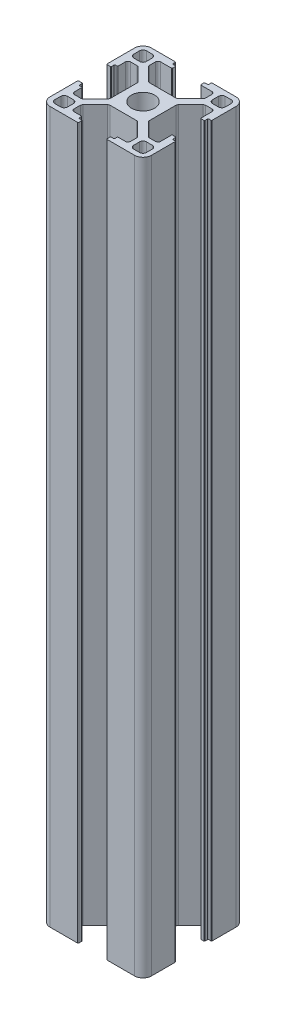
SolidWorks part; units mm, degrees
ref_plane "Front Plane" through (0, 0, 0) normal (0, 0, 1) x (1, 0, 0)
ref_plane "Top Plane" through (0, 0, 0) normal (0, 1, 0) x (1, 0, 0)
ref_plane "Right Plane" through (0, 0, 0) normal (1, 0, 0) x (0, 0, -1)
sketch "Sketch2" plane through (0, -1630.4411, 0) normal (0, 1, 0) x (1, 0, 0)
  line L4 (-1206.0668, -28.55) -> (-1204.3168, -28.55)
  line L5 (-1203.3168, -27.55) -> (-1203.3168, -25.8)
  line L6 (-1204.3168, -24.8) -> (-1206.0668, -24.8)
  line L7 (-1207.0668, -25.8) -> (-1207.0668, -27.55)
  line L8 (-1206.0668, -28.55) -> (-1204.3168, -28.55)
  line L9 (-1203.3168, -27.55) -> (-1203.3168, -25.8)
  line L10 (-1204.3168, -24.8) -> (-1206.0668, -24.8)
  line L11 (-1207.0668, -25.8) -> (-1207.0668, -27.55)
  line L12 (-1206.0668, -5.2) -> (-1204.3168, -5.2)
  line L13 (-1203.3168, -4.2) -> (-1203.3168, -2.45)
  line L14 (-1204.3168, -1.45) -> (-1206.0668, -1.45)
  line L15 (-1207.0668, -2.45) -> (-1207.0668, -4.2)
  line L16 (-1206.0668, -5.2) -> (-1204.3168, -5.2)
  line L17 (-1203.3168, -4.2) -> (-1203.3168, -2.45)
  line L18 (-1204.3168, -1.45) -> (-1206.0668, -1.45)
  line L19 (-1207.0668, -2.45) -> (-1207.0668, -4.2)
  line L20 (-1180.9668, -24.8) -> (-1182.7168, -24.8)
  line L21 (-1183.7168, -25.8) -> (-1183.7168, -27.55)
  line L22 (-1182.7168, -28.55) -> (-1180.9668, -28.55)
  line L23 (-1179.9668, -27.55) -> (-1179.9668, -25.8)
  line L24 (-1180.9668, -24.8) -> (-1182.7168, -24.8)
  line L25 (-1183.7168, -25.8) -> (-1183.7168, -27.55)
  line L26 (-1182.7168, -28.55) -> (-1180.9668, -28.55)
  line L27 (-1179.9668, -27.55) -> (-1179.9668, -25.8)
  line L28 (-1182.7168, -5.2) -> (-1180.9668, -5.2)
  line L29 (-1179.9668, -4.2) -> (-1179.9668, -2.45)
  line L30 (-1180.9668, -1.45) -> (-1182.7168, -1.45)
  line L31 (-1183.7168, -2.45) -> (-1183.7168, -4.2)
  line L32 (-1182.7168, -5.2) -> (-1180.9668, -5.2)
  line L33 (-1179.9668, -4.2) -> (-1179.9668, -2.45)
  line L34 (-1180.9668, -1.45) -> (-1182.7168, -1.45)
  line L35 (-1183.7168, -2.45) -> (-1183.7168, -4.2)
  line L60 (-1199.0168, 0) -> (-1206.0168, 0)
  line L61 (-1198.8168, -0.8) -> (-1198.8168, -0.2)
  line L62 (-1197.9168, -1) -> (-1198.6168, -1)
  line L63 (-1197.7168, -2) -> (-1197.7168, -1.2)
  line L64 (-1201.1168, -2.2) -> (-1197.9168, -2.2)
  line L65 (-1201.8668, -4.7837) -> (-1201.8668, -2.95)
  line L66 (-1197.9808, -8.9803) -> (-1201.6471, -5.314)
  line L67 (-1189.5831, -9.2) -> (-1197.4505, -9.2)
  line L68 (-1185.3865, -5.314) -> (-1189.0528, -8.9803)
  line L69 (-1185.1668, -2.95) -> (-1185.1668, -4.7837)
  line L70 (-1189.1168, -2.2) -> (-1185.9168, -2.2)
  line L71 (-1189.3168, -1.2) -> (-1189.3168, -2)
  line L72 (-1188.4168, -1) -> (-1189.1168, -1)
  line L73 (-1188.2168, -0.2) -> (-1188.2168, -0.8)
  line L74 (-1181.0168, 0) -> (-1188.0168, 0)
  line L75 (-1178.5168, -9.5) -> (-1178.5168, -2.5)
  line L76 (-1179.3168, -9.7) -> (-1178.7168, -9.7)
  line L77 (-1179.5168, -10.6) -> (-1179.5168, -9.9)
  line L78 (-1180.5168, -10.8) -> (-1179.7168, -10.8)
  line L79 (-1180.7168, -7.4) -> (-1180.7168, -10.6)
  line L80 (-1183.3005, -6.65) -> (-1181.4668, -6.65)
  line L81 (-1187.4971, -10.536) -> (-1183.8308, -6.8697)
  line L82 (-1187.7168, -18.9337) -> (-1187.7168, -11.0663)
  line L83 (-1183.8308, -23.1303) -> (-1187.4971, -19.464)
  line L84 (-1181.4668, -23.35) -> (-1183.3005, -23.35)
  line L85 (-1180.7168, -19.4) -> (-1180.7168, -22.6)
  line L86 (-1179.7168, -19.2) -> (-1180.5168, -19.2)
  line L87 (-1179.5168, -20.1) -> (-1179.5168, -19.4)
  line L88 (-1178.7168, -20.3) -> (-1179.3168, -20.3)
  line L89 (-1178.5168, -27.5) -> (-1178.5168, -20.5)
  line L90 (-1189.1168, -30) -> (-1181.0168, -30)
  line L91 (-1189.3168, -29) -> (-1189.3168, -29.8)
  line L92 (-1188.4168, -28.8) -> (-1189.1168, -28.8)
  line L93 (-1188.2168, -28) -> (-1188.2168, -28.6)
  line L94 (-1185.9168, -27.8) -> (-1188.0168, -27.8)
  line L95 (-1185.1668, -25.2163) -> (-1185.1668, -27.05)
  line L96 (-1189.0528, -21.0197) -> (-1185.3865, -24.686)
  line L97 (-1197.4505, -20.8) -> (-1189.5831, -20.8)
  line L98 (-1201.6471, -24.686) -> (-1197.9808, -21.0197)
  line L99 (-1201.8668, -27.05) -> (-1201.8668, -25.2163)
  line L100 (-1199.0168, -27.8) -> (-1201.1168, -27.8)
  line L101 (-1198.8168, -28.6) -> (-1198.8168, -28)
  line L102 (-1197.9168, -28.8) -> (-1198.6168, -28.8)
  line L103 (-1197.7168, -29.8) -> (-1197.7168, -29)
  line L104 (-1206.0168, -30) -> (-1197.9168, -30)
  line L105 (-1208.5168, -19.4) -> (-1208.5168, -27.5)
  line L106 (-1207.3844, -19.2) -> (-1208.3168, -19.2)
  line L107 (-1207.1844, -20.1) -> (-1207.1844, -19.4)
  line L108 (-1206.3844, -20.3) -> (-1206.9844, -20.3)
  line L109 (-1206.1844, -22.6) -> (-1206.1844, -20.5)
  line L110 (-1203.6007, -23.35) -> (-1205.4344, -23.35)
  line L111 (-1199.404, -19.464) -> (-1203.0703, -23.1303)
  line L112 (-1199.1844, -11.0663) -> (-1199.1844, -18.9337)
  line L113 (-1203.0703, -6.8697) -> (-1199.404, -10.536)
  line L114 (-1205.5668, -6.65) -> (-1203.6007, -6.65)
  line L115 (-1206.3168, -9.5) -> (-1206.3168, -7.4)
  line L116 (-1206.9844, -9.7) -> (-1206.5168, -9.7)
  line L117 (-1207.1844, -10.6) -> (-1207.1844, -9.9)
  line L118 (-1208.3168, -10.8) -> (-1207.3844, -10.8)
  line L119 (-1208.5168, -2.5) -> (-1208.5168, -10.6)
  line L120 (-1199.0168, 0) -> (-1206.0168, 0)
  line L121 (-1198.8168, -0.8) -> (-1198.8168, -0.2)
  line L122 (-1197.9168, -1) -> (-1198.6168, -1)
  line L123 (-1197.7168, -2) -> (-1197.7168, -1.2)
  line L124 (-1201.1168, -2.2) -> (-1197.9168, -2.2)
  line L125 (-1201.8668, -4.7837) -> (-1201.8668, -2.95)
  line L126 (-1197.9808, -8.9803) -> (-1201.6471, -5.314)
  line L127 (-1189.5831, -9.2) -> (-1197.4505, -9.2)
  line L128 (-1185.3865, -5.314) -> (-1189.0528, -8.9803)
  line L129 (-1185.1668, -2.95) -> (-1185.1668, -4.7837)
  line L130 (-1189.1168, -2.2) -> (-1185.9168, -2.2)
  line L131 (-1189.3168, -1.2) -> (-1189.3168, -2)
  line L132 (-1188.4168, -1) -> (-1189.1168, -1)
  line L133 (-1188.2168, -0.2) -> (-1188.2168, -0.8)
  line L134 (-1181.0168, 0) -> (-1188.0168, 0)
  line L135 (-1178.5168, -9.5) -> (-1178.5168, -2.5)
  line L136 (-1179.3168, -9.7) -> (-1178.7168, -9.7)
  line L137 (-1179.5168, -10.6) -> (-1179.5168, -9.9)
  line L138 (-1180.5168, -10.8) -> (-1179.7168, -10.8)
  line L139 (-1180.7168, -7.4) -> (-1180.7168, -10.6)
  line L140 (-1183.3005, -6.65) -> (-1181.4668, -6.65)
  line L141 (-1187.4971, -10.536) -> (-1183.8308, -6.8697)
  line L142 (-1187.7168, -18.9337) -> (-1187.7168, -11.0663)
  line L143 (-1183.8308, -23.1303) -> (-1187.4971, -19.464)
  line L144 (-1181.4668, -23.35) -> (-1183.3005, -23.35)
  line L145 (-1180.7168, -19.4) -> (-1180.7168, -22.6)
  line L146 (-1179.7168, -19.2) -> (-1180.5168, -19.2)
  line L147 (-1179.5168, -20.1) -> (-1179.5168, -19.4)
  line L148 (-1178.7168, -20.3) -> (-1179.3168, -20.3)
  line L149 (-1178.5168, -27.5) -> (-1178.5168, -20.5)
  line L150 (-1189.1168, -30) -> (-1181.0168, -30)
  line L151 (-1189.3168, -29) -> (-1189.3168, -29.8)
  line L152 (-1188.4168, -28.8) -> (-1189.1168, -28.8)
  line L153 (-1188.2168, -28) -> (-1188.2168, -28.6)
  line L154 (-1185.9168, -27.8) -> (-1188.0168, -27.8)
  line L155 (-1185.1668, -25.2163) -> (-1185.1668, -27.05)
  line L156 (-1189.0528, -21.0197) -> (-1185.3865, -24.686)
  line L157 (-1197.4505, -20.8) -> (-1189.5831, -20.8)
  line L158 (-1201.6471, -24.686) -> (-1197.9808, -21.0197)
  line L159 (-1201.8668, -27.05) -> (-1201.8668, -25.2163)
  line L160 (-1199.0168, -27.8) -> (-1201.1168, -27.8)
  line L161 (-1198.8168, -28.6) -> (-1198.8168, -28)
  line L162 (-1197.9168, -28.8) -> (-1198.6168, -28.8)
  line L163 (-1197.7168, -29.8) -> (-1197.7168, -29)
  line L164 (-1206.0168, -30) -> (-1197.9168, -30)
  line L165 (-1208.5168, -19.4) -> (-1208.5168, -27.5)
  line L166 (-1207.3844, -19.2) -> (-1208.3168, -19.2)
  line L167 (-1207.1844, -20.1) -> (-1207.1844, -19.4)
  line L168 (-1206.3844, -20.3) -> (-1206.9844, -20.3)
  line L169 (-1206.1844, -22.6) -> (-1206.1844, -20.5)
  line L170 (-1203.6007, -23.35) -> (-1205.4344, -23.35)
  line L171 (-1199.404, -19.464) -> (-1203.0703, -23.1303)
  line L172 (-1199.1844, -11.0663) -> (-1199.1844, -18.9337)
  line L173 (-1203.0703, -6.8697) -> (-1199.404, -10.536)
  line L174 (-1205.5668, -6.65) -> (-1203.6007, -6.65)
  line L175 (-1206.3168, -9.5) -> (-1206.3168, -7.4)
  line L176 (-1206.9844, -9.7) -> (-1206.5168, -9.7)
  line L177 (-1207.1844, -10.6) -> (-1207.1844, -9.9)
  line L178 (-1208.3168, -10.8) -> (-1207.3844, -10.8)
  line L179 (-1208.5168, -2.5) -> (-1208.5168, -10.6)
  arc A2 (-1193.5168, -11.6) -> (-1193.5168, -18.4) centre (-1193.5168, -15) ccw
  arc A3 (-1193.5168, -18.4) -> (-1193.5168, -11.6) centre (-1193.5168, -15) ccw
  arc A4 (-1207.0668, -27.55) -> (-1206.0668, -28.55) centre (-1206.0668, -27.55) ccw
  arc A5 (-1204.3168, -28.55) -> (-1203.3168, -27.55) centre (-1204.3168, -27.55) ccw
  arc A6 (-1203.3168, -25.8) -> (-1204.3168, -24.8) centre (-1204.3168, -25.8) ccw
  arc A7 (-1206.0668, -24.8) -> (-1207.0668, -25.8) centre (-1206.0668, -25.8) ccw
  arc A8 (-1207.0668, -27.55) -> (-1206.0668, -28.55) centre (-1206.0668, -27.55) ccw
  arc A9 (-1204.3168, -28.55) -> (-1203.3168, -27.55) centre (-1204.3168, -27.55) ccw
  arc A10 (-1203.3168, -25.8) -> (-1204.3168, -24.8) centre (-1204.3168, -25.8) ccw
  arc A11 (-1206.0668, -24.8) -> (-1207.0668, -25.8) centre (-1206.0668, -25.8) ccw
  arc A12 (-1207.0668, -4.2) -> (-1206.0668, -5.2) centre (-1206.0668, -4.2) ccw
  arc A13 (-1204.3168, -5.2) -> (-1203.3168, -4.2) centre (-1204.3168, -4.2) ccw
  arc A14 (-1203.3168, -2.45) -> (-1204.3168, -1.45) centre (-1204.3168, -2.45) ccw
  arc A15 (-1206.0668, -1.45) -> (-1207.0668, -2.45) centre (-1206.0668, -2.45) ccw
  arc A16 (-1207.0668, -4.2) -> (-1206.0668, -5.2) centre (-1206.0668, -4.2) ccw
  arc A17 (-1204.3168, -5.2) -> (-1203.3168, -4.2) centre (-1204.3168, -4.2) ccw
  arc A18 (-1203.3168, -2.45) -> (-1204.3168, -1.45) centre (-1204.3168, -2.45) ccw
  arc A19 (-1206.0668, -1.45) -> (-1207.0668, -2.45) centre (-1206.0668, -2.45) ccw
  arc A20 (-1193.5168, -11.6) -> (-1193.5168, -18.4) centre (-1193.5168, -15) ccw
  arc A21 (-1193.5168, -18.4) -> (-1193.5168, -11.6) centre (-1193.5168, -15) ccw
  arc A24 (-1179.9668, -25.8) -> (-1180.9668, -24.8) centre (-1180.9668, -25.8) ccw
  arc A25 (-1182.7168, -24.8) -> (-1183.7168, -25.8) centre (-1182.7168, -25.8) ccw
  arc A26 (-1183.7168, -27.55) -> (-1182.7168, -28.55) centre (-1182.7168, -27.55) ccw
  arc A27 (-1180.9668, -28.55) -> (-1179.9668, -27.55) centre (-1180.9668, -27.55) ccw
  arc A28 (-1179.9668, -25.8) -> (-1180.9668, -24.8) centre (-1180.9668, -25.8) ccw
  arc A29 (-1182.7168, -24.8) -> (-1183.7168, -25.8) centre (-1182.7168, -25.8) ccw
  arc A30 (-1183.7168, -27.55) -> (-1182.7168, -28.55) centre (-1182.7168, -27.55) ccw
  arc A31 (-1180.9668, -28.55) -> (-1179.9668, -27.55) centre (-1180.9668, -27.55) ccw
  arc A32 (-1183.7168, -4.2) -> (-1182.7168, -5.2) centre (-1182.7168, -4.2) ccw
  arc A33 (-1180.9668, -5.2) -> (-1179.9668, -4.2) centre (-1180.9668, -4.2) ccw
  arc A34 (-1179.9668, -2.45) -> (-1180.9668, -1.45) centre (-1180.9668, -2.45) ccw
  arc A35 (-1182.7168, -1.45) -> (-1183.7168, -2.45) centre (-1182.7168, -2.45) ccw
  arc A36 (-1183.7168, -4.2) -> (-1182.7168, -5.2) centre (-1182.7168, -4.2) ccw
  arc A37 (-1180.9668, -5.2) -> (-1179.9668, -4.2) centre (-1180.9668, -4.2) ccw
  arc A38 (-1179.9668, -2.45) -> (-1180.9668, -1.45) centre (-1180.9668, -2.45) ccw
  arc A39 (-1182.7168, -1.45) -> (-1183.7168, -2.45) centre (-1182.7168, -2.45) ccw
  arc A60 (-1206.0168, 0) -> (-1208.5168, -2.5) centre (-1206.0168, -2.5) ccw
  arc A61 (-1198.8168, -0.2) -> (-1199.0168, 0) centre (-1199.0168, -0.2) ccw
  arc A62 (-1198.8168, -0.8) -> (-1198.6168, -1) centre (-1198.6168, -0.8) ccw
  arc A63 (-1197.7168, -1.2) -> (-1197.9168, -1) centre (-1197.9168, -1.2) ccw
  arc A64 (-1197.9168, -2.2) -> (-1197.7168, -2) centre (-1197.9168, -2) ccw
  arc A65 (-1201.1168, -2.2) -> (-1201.8668, -2.95) centre (-1201.1168, -2.95) ccw
  arc A66 (-1201.8668, -4.7837) -> (-1201.6471, -5.314) centre (-1201.1168, -4.7837) ccw
  arc A67 (-1197.9808, -8.9803) -> (-1197.4505, -9.2) centre (-1197.4505, -8.45) ccw
  arc A68 (-1189.5831, -9.2) -> (-1189.0528, -8.9803) centre (-1189.5831, -8.45) ccw
  arc A69 (-1185.3865, -5.314) -> (-1185.1668, -4.7837) centre (-1185.9168, -4.7837) ccw
  arc A70 (-1185.1668, -2.95) -> (-1185.9168, -2.2) centre (-1185.9168, -2.95) ccw
  arc A71 (-1189.3168, -2) -> (-1189.1168, -2.2) centre (-1189.1168, -2) ccw
  arc A72 (-1189.1168, -1) -> (-1189.3168, -1.2) centre (-1189.1168, -1.2) ccw
  arc A73 (-1188.4168, -1) -> (-1188.2168, -0.8) centre (-1188.4168, -0.8) ccw
  arc A74 (-1188.0168, 0) -> (-1188.2168, -0.2) centre (-1188.0168, -0.2) ccw
  arc A75 (-1178.5168, -2.5) -> (-1181.0168, 0) centre (-1181.0168, -2.5) ccw
  arc A76 (-1178.7168, -9.7) -> (-1178.5168, -9.5) centre (-1178.7168, -9.5) ccw
  arc A77 (-1179.3168, -9.7) -> (-1179.5168, -9.9) centre (-1179.3168, -9.9) ccw
  arc A78 (-1179.7168, -10.8) -> (-1179.5168, -10.6) centre (-1179.7168, -10.6) ccw
  arc A79 (-1180.7168, -10.6) -> (-1180.5168, -10.8) centre (-1180.5168, -10.6) ccw
  arc A80 (-1180.7168, -7.4) -> (-1181.4668, -6.65) centre (-1181.4668, -7.4) ccw
  arc A81 (-1183.3005, -6.65) -> (-1183.8308, -6.8697) centre (-1183.3005, -7.4) ccw
  arc A82 (-1187.4971, -10.536) -> (-1187.7168, -11.0663) centre (-1186.9668, -11.0663) ccw
  arc A83 (-1187.7168, -18.9337) -> (-1187.4971, -19.464) centre (-1186.9668, -18.9337) ccw
  arc A84 (-1183.8308, -23.1303) -> (-1183.3005, -23.35) centre (-1183.3005, -22.6) ccw
  arc A85 (-1181.4668, -23.35) -> (-1180.7168, -22.6) centre (-1181.4668, -22.6) ccw
  arc A86 (-1180.5168, -19.2) -> (-1180.7168, -19.4) centre (-1180.5168, -19.4) ccw
  arc A87 (-1179.5168, -19.4) -> (-1179.7168, -19.2) centre (-1179.7168, -19.4) ccw
  arc A88 (-1179.5168, -20.1) -> (-1179.3168, -20.3) centre (-1179.3168, -20.1) ccw
  arc A89 (-1178.5168, -20.5) -> (-1178.7168, -20.3) centre (-1178.7168, -20.5) ccw
  arc A90 (-1181.0168, -30) -> (-1178.5168, -27.5) centre (-1181.0168, -27.5) ccw
  arc A91 (-1189.3168, -29.8) -> (-1189.1168, -30) centre (-1189.1168, -29.8) ccw
  arc A92 (-1189.1168, -28.8) -> (-1189.3168, -29) centre (-1189.1168, -29) ccw
  arc A93 (-1188.4168, -28.8) -> (-1188.2168, -28.6) centre (-1188.4168, -28.6) ccw
  arc A94 (-1188.0168, -27.8) -> (-1188.2168, -28) centre (-1188.0168, -28) ccw
  arc A95 (-1185.9168, -27.8) -> (-1185.1668, -27.05) centre (-1185.9168, -27.05) ccw
  arc A96 (-1185.1668, -25.2163) -> (-1185.3865, -24.686) centre (-1185.9168, -25.2163) ccw
  arc A97 (-1189.0528, -21.0197) -> (-1189.5831, -20.8) centre (-1189.5831, -21.55) ccw
  arc A98 (-1197.4505, -20.8) -> (-1197.9808, -21.0197) centre (-1197.4505, -21.55) ccw
  arc A99 (-1201.6471, -24.686) -> (-1201.8668, -25.2163) centre (-1201.1168, -25.2163) ccw
  arc A100 (-1201.8668, -27.05) -> (-1201.1168, -27.8) centre (-1201.1168, -27.05) ccw
  arc A101 (-1198.8168, -28) -> (-1199.0168, -27.8) centre (-1199.0168, -28) ccw
  arc A102 (-1198.8168, -28.6) -> (-1198.6168, -28.8) centre (-1198.6168, -28.6) ccw
  arc A103 (-1197.7168, -29) -> (-1197.9168, -28.8) centre (-1197.9168, -29) ccw
  arc A104 (-1197.9168, -30) -> (-1197.7168, -29.8) centre (-1197.9168, -29.8) ccw
  arc A105 (-1208.5168, -27.5) -> (-1206.0168, -30) centre (-1206.0168, -27.5) ccw
  arc A106 (-1208.3168, -19.2) -> (-1208.5168, -19.4) centre (-1208.3168, -19.4) ccw
  arc A107 (-1207.1844, -19.4) -> (-1207.3844, -19.2) centre (-1207.3844, -19.4) ccw
  arc A108 (-1207.1844, -20.1) -> (-1206.9844, -20.3) centre (-1206.9844, -20.1) ccw
  arc A109 (-1206.1844, -20.5) -> (-1206.3844, -20.3) centre (-1206.3844, -20.5) ccw
  arc A110 (-1206.1844, -22.6) -> (-1205.4344, -23.35) centre (-1205.4344, -22.6) ccw
  arc A111 (-1203.6007, -23.35) -> (-1203.0703, -23.1303) centre (-1203.6007, -22.6) ccw
  arc A112 (-1199.404, -19.464) -> (-1199.1844, -18.9337) centre (-1199.9344, -18.9337) ccw
  arc A113 (-1199.1844, -11.0663) -> (-1199.404, -10.536) centre (-1199.9344, -11.0663) ccw
  arc A114 (-1203.0703, -6.8697) -> (-1203.6007, -6.65) centre (-1203.6007, -7.4) ccw
  arc A115 (-1205.5668, -6.65) -> (-1206.3168, -7.4) centre (-1205.5668, -7.4) ccw
  arc A116 (-1206.5168, -9.7) -> (-1206.3168, -9.5) centre (-1206.5168, -9.5) ccw
  arc A117 (-1206.9844, -9.7) -> (-1207.1844, -9.9) centre (-1206.9844, -9.9) ccw
  arc A118 (-1207.3844, -10.8) -> (-1207.1844, -10.6) centre (-1207.3844, -10.6) ccw
  arc A119 (-1208.5168, -10.6) -> (-1208.3168, -10.8) centre (-1208.3168, -10.6) ccw
  arc A120 (-1206.0168, 0) -> (-1208.5168, -2.5) centre (-1206.0168, -2.5) ccw
  arc A121 (-1198.8168, -0.2) -> (-1199.0168, 0) centre (-1199.0168, -0.2) ccw
  arc A122 (-1198.8168, -0.8) -> (-1198.6168, -1) centre (-1198.6168, -0.8) ccw
  arc A123 (-1197.7168, -1.2) -> (-1197.9168, -1) centre (-1197.9168, -1.2) ccw
  arc A124 (-1197.9168, -2.2) -> (-1197.7168, -2) centre (-1197.9168, -2) ccw
  arc A125 (-1201.1168, -2.2) -> (-1201.8668, -2.95) centre (-1201.1168, -2.95) ccw
  arc A126 (-1201.8668, -4.7837) -> (-1201.6471, -5.314) centre (-1201.1168, -4.7837) ccw
  arc A127 (-1197.9808, -8.9803) -> (-1197.4505, -9.2) centre (-1197.4505, -8.45) ccw
  arc A128 (-1189.5831, -9.2) -> (-1189.0528, -8.9803) centre (-1189.5831, -8.45) ccw
  arc A129 (-1185.3865, -5.314) -> (-1185.1668, -4.7837) centre (-1185.9168, -4.7837) ccw
  arc A130 (-1185.1668, -2.95) -> (-1185.9168, -2.2) centre (-1185.9168, -2.95) ccw
  arc A131 (-1189.3168, -2) -> (-1189.1168, -2.2) centre (-1189.1168, -2) ccw
  arc A132 (-1189.1168, -1) -> (-1189.3168, -1.2) centre (-1189.1168, -1.2) ccw
  arc A133 (-1188.4168, -1) -> (-1188.2168, -0.8) centre (-1188.4168, -0.8) ccw
  arc A134 (-1188.0168, 0) -> (-1188.2168, -0.2) centre (-1188.0168, -0.2) ccw
  arc A135 (-1178.5168, -2.5) -> (-1181.0168, 0) centre (-1181.0168, -2.5) ccw
  arc A136 (-1178.7168, -9.7) -> (-1178.5168, -9.5) centre (-1178.7168, -9.5) ccw
  arc A137 (-1179.3168, -9.7) -> (-1179.5168, -9.9) centre (-1179.3168, -9.9) ccw
  arc A138 (-1179.7168, -10.8) -> (-1179.5168, -10.6) centre (-1179.7168, -10.6) ccw
  arc A139 (-1180.7168, -10.6) -> (-1180.5168, -10.8) centre (-1180.5168, -10.6) ccw
  arc A140 (-1180.7168, -7.4) -> (-1181.4668, -6.65) centre (-1181.4668, -7.4) ccw
  arc A141 (-1183.3005, -6.65) -> (-1183.8308, -6.8697) centre (-1183.3005, -7.4) ccw
  arc A142 (-1187.4971, -10.536) -> (-1187.7168, -11.0663) centre (-1186.9668, -11.0663) ccw
  arc A143 (-1187.7168, -18.9337) -> (-1187.4971, -19.464) centre (-1186.9668, -18.9337) ccw
  arc A144 (-1183.8308, -23.1303) -> (-1183.3005, -23.35) centre (-1183.3005, -22.6) ccw
  arc A145 (-1181.4668, -23.35) -> (-1180.7168, -22.6) centre (-1181.4668, -22.6) ccw
  arc A146 (-1180.5168, -19.2) -> (-1180.7168, -19.4) centre (-1180.5168, -19.4) ccw
  arc A147 (-1179.5168, -19.4) -> (-1179.7168, -19.2) centre (-1179.7168, -19.4) ccw
  arc A148 (-1179.5168, -20.1) -> (-1179.3168, -20.3) centre (-1179.3168, -20.1) ccw
  arc A149 (-1178.5168, -20.5) -> (-1178.7168, -20.3) centre (-1178.7168, -20.5) ccw
  arc A150 (-1181.0168, -30) -> (-1178.5168, -27.5) centre (-1181.0168, -27.5) ccw
  arc A151 (-1189.3168, -29.8) -> (-1189.1168, -30) centre (-1189.1168, -29.8) ccw
  arc A152 (-1189.1168, -28.8) -> (-1189.3168, -29) centre (-1189.1168, -29) ccw
  arc A153 (-1188.4168, -28.8) -> (-1188.2168, -28.6) centre (-1188.4168, -28.6) ccw
  arc A154 (-1188.0168, -27.8) -> (-1188.2168, -28) centre (-1188.0168, -28) ccw
  arc A155 (-1185.9168, -27.8) -> (-1185.1668, -27.05) centre (-1185.9168, -27.05) ccw
  arc A156 (-1185.1668, -25.2163) -> (-1185.3865, -24.686) centre (-1185.9168, -25.2163) ccw
  arc A157 (-1189.0528, -21.0197) -> (-1189.5831, -20.8) centre (-1189.5831, -21.55) ccw
  arc A158 (-1197.4505, -20.8) -> (-1197.9808, -21.0197) centre (-1197.4505, -21.55) ccw
  arc A159 (-1201.6471, -24.686) -> (-1201.8668, -25.2163) centre (-1201.1168, -25.2163) ccw
  arc A160 (-1201.8668, -27.05) -> (-1201.1168, -27.8) centre (-1201.1168, -27.05) ccw
  arc A161 (-1198.8168, -28) -> (-1199.0168, -27.8) centre (-1199.0168, -28) ccw
  arc A162 (-1198.8168, -28.6) -> (-1198.6168, -28.8) centre (-1198.6168, -28.6) ccw
  arc A163 (-1197.7168, -29) -> (-1197.9168, -28.8) centre (-1197.9168, -29) ccw
  arc A164 (-1197.9168, -30) -> (-1197.7168, -29.8) centre (-1197.9168, -29.8) ccw
  arc A165 (-1208.5168, -27.5) -> (-1206.0168, -30) centre (-1206.0168, -27.5) ccw
  arc A166 (-1208.3168, -19.2) -> (-1208.5168, -19.4) centre (-1208.3168, -19.4) ccw
  arc A167 (-1207.1844, -19.4) -> (-1207.3844, -19.2) centre (-1207.3844, -19.4) ccw
  arc A168 (-1207.1844, -20.1) -> (-1206.9844, -20.3) centre (-1206.9844, -20.1) ccw
  arc A169 (-1206.1844, -20.5) -> (-1206.3844, -20.3) centre (-1206.3844, -20.5) ccw
  arc A170 (-1206.1844, -22.6) -> (-1205.4344, -23.35) centre (-1205.4344, -22.6) ccw
  arc A171 (-1203.6007, -23.35) -> (-1203.0703, -23.1303) centre (-1203.6007, -22.6) ccw
  arc A172 (-1199.404, -19.464) -> (-1199.1844, -18.9337) centre (-1199.9344, -18.9337) ccw
  arc A173 (-1199.1844, -11.0663) -> (-1199.404, -10.536) centre (-1199.9344, -11.0663) ccw
  arc A174 (-1203.0703, -6.8697) -> (-1203.6007, -6.65) centre (-1203.6007, -7.4) ccw
  arc A175 (-1205.5668, -6.65) -> (-1206.3168, -7.4) centre (-1205.5668, -7.4) ccw
  arc A176 (-1206.5168, -9.7) -> (-1206.3168, -9.5) centre (-1206.5168, -9.5) ccw
  arc A177 (-1206.9844, -9.7) -> (-1207.1844, -9.9) centre (-1206.9844, -9.9) ccw
  arc A178 (-1207.3844, -10.8) -> (-1207.1844, -10.6) centre (-1207.3844, -10.6) ccw
  arc A179 (-1208.5168, -10.6) -> (-1208.3168, -10.8) centre (-1208.3168, -10.6) ccw
  dimension "D1" = 0
  dimension "D2" = 0
  dimension "D3" = 0
  dimension "D4" = 0
  dimension "D5" = 0
  dimension "D6" = 0
extrude "Boss-Extrude3" add sketch "Sketch2" along normal offset from surface (210.44 mm away) 1 from offset 1
